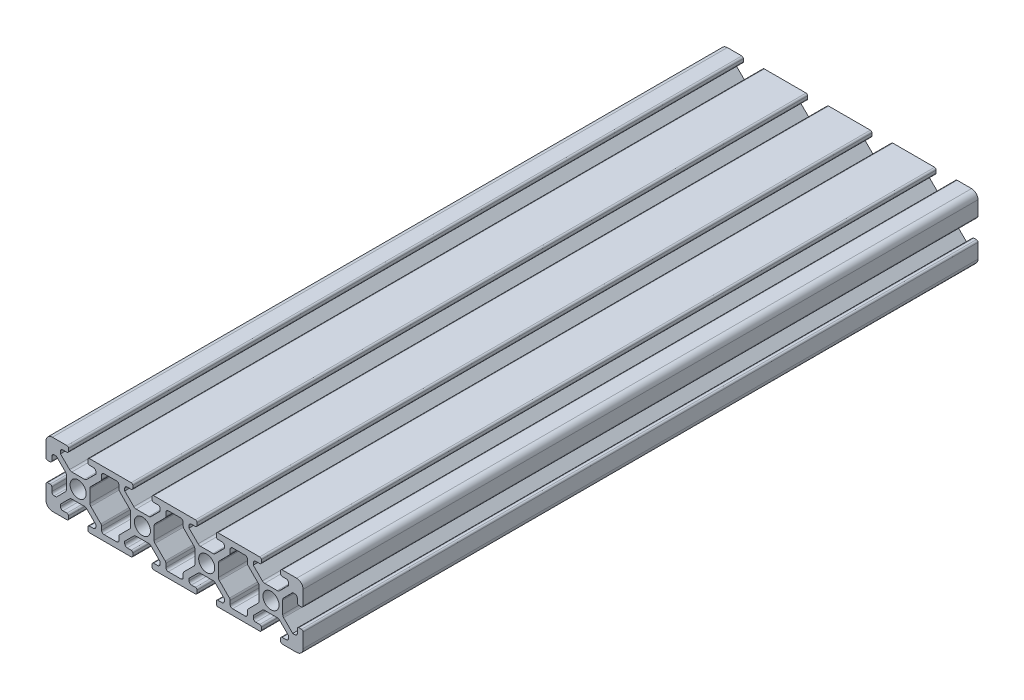
SolidWorks part; units mm, degrees
ref_plane "Front Plane" through (0, 0, 0) normal (0, 0, 1) x (1, 0, 0)
ref_plane "Top Plane" through (0, 0, 0) normal (0, 1, 0) x (1, 0, 0)
ref_plane "Right Plane" through (0, 0, 0) normal (1, 0, 0) x (0, 0, -1)
sketch "Sketch1" plane through (0, 0, 0) normal (0, 0, 1) x (1, 0, 0)
  line L0 (-38, -10) -> (-33.5, -10)
  line L1 (40, -8) -> (40, -3.5)
  line L2 (38, 10) -> (33.5, 10)
  line L3 (-40, 8) -> (-40, 3.5)
  line L4 (-7, 9.5) -> (-7, 8.7)
  line L5 (-13, 9.5) -> (-13, 8.7)
  line L6 (-33, 9.5) -> (-33, 8.7)
  line L7 (-27, 9.5) -> (-27, 8.7)
  line L8 (-33.5, 10) -> (-38, 10)
  line L9 (13, 9.5) -> (13, 8.7)
  line L10 (7, 9.5) -> (7, 8.7)
  line L11 (33, 9.5) -> (33, 8.7)
  line L12 (27, 9.5) -> (27, 8.7)
  line L13 (-7, -8.7) -> (-7, -9.5)
  line L14 (-13, -8.7) -> (-13, -9.5)
  line L15 (13, -8.7) -> (13, -9.5)
  line L16 (7, -8.7) -> (7, -9.5)
  line L17 (33, -8.7) -> (33, -9.5)
  line L18 (27, -8.7) -> (27, -9.5)
  line L19 (-27, -8.7) -> (-27, -9.5)
  line L20 (-33, -8.7) -> (-33, -9.5)
  line L21 (-26.5, 10) -> (-13.5, 10) construction
  line L22 (-13.5, 10) -> (-26.5, 10)
  line L23 (6.5, 10) -> (-6.5, 10)
  line L24 (26.5, 10) -> (13.5, 10)
  line L25 (33.5, -10) -> (38, -10)
  line L26 (13.5, -10) -> (26.5, -10)
  line L27 (-6.5, -10) -> (6.5, -10)
  line L28 (-26.5, -10) -> (-13.5, -10)
  line L29 (39.5, 3) -> (38.7, 3)
  line L30 (39.5, -3) -> (38.7, -3)
  line L31 (-39.5, 3) -> (-38.7, 3)
  line L32 (-39.5, -3) -> (-38.7, -3)
  line L33 (-40, -3.5) -> (-40, -8)
  line L34 (40, 3.5) -> (40, 8)
  line L35 (-38.2, 3.5) -> (-38.2, 4.75)
  line L36 (-34.75, 8.2) -> (-33.5, 8.2)
  line L37 (38.2, 4.75) -> (38.2, 3.5)
  line L38 (34.75, -8.2) -> (33.5, -8.2)
  line L39 (-38.2, -4.75) -> (-38.2, -3.5)
  line L40 (-26.5, 8.2) -> (-25.25, 8.2)
  line L41 (-33.5, -8.2) -> (-34.75, -8.2)
  line L42 (-6.5, 8.2) -> (-5.25, 8.2)
  line L43 (-13.5, -8.2) -> (-14.75, -8.2)
  line L44 (13.5, 8.2) -> (14.75, 8.2)
  line L45 (6.5, -8.2) -> (5.25, -8.2)
  line L46 (33.5, 8.2) -> (34.75, 8.2)
  line L47 (26.5, -8.2) -> (25.25, -8.2)
  line L48 (38.2, -3.5) -> (38.2, -4.75)
  line L49 (-27.3299, 3.9429) -> (-24.5, 6.7728)
  line L50 (-27.3299, -3.9429) -> (-24.5, -6.7728)
  line L51 (-7.3299, 3.9429) -> (-4.5, 6.7728)
  line L52 (-6.0571, 2.6701) -> (-2.9197, 5.8075)
  line L53 (-12.6701, 3.9429) -> (-15.5, 6.7728)
  line L54 (-17.0803, 5.8075) -> (-13.9429, 2.6701)
  line L55 (-12.6701, -3.9429) -> (-15.5, -6.7728)
  line L56 (-17.0803, -5.8075) -> (-13.9429, -2.6701)
  line L57 (7.3299, 3.9429) -> (4.5, 6.7728)
  line L58 (2.9197, 5.8075) -> (6.0571, 2.6701)
  line L59 (7.3299, -3.9429) -> (4.5, -6.7728)
  line L60 (2.9197, -5.8075) -> (6.0571, -2.6701)
  line L61 (27.3299, 3.9429) -> (24.5, 6.7728)
  line L62 (22.9197, 5.8075) -> (26.0571, 2.6701)
  line L63 (27.3299, -3.9429) -> (24.5, -6.7728)
  line L64 (22.9197, -5.8075) -> (26.0571, -2.6701)
  line L65 (-6.0571, -2.6701) -> (-2.9197, -5.8075)
  line L66 (-26.0571, 2.6701) -> (-22.9197, 5.8075)
  line L67 (-33.9429, -2.6701) -> (-36.7728, -5.5)
  line L68 (-32.6701, -3.9429) -> (-35.5, -6.7728)
  line L69 (-32.6701, 3.9429) -> (-35.5, 6.7728)
  line L70 (-7.3299, -3.9429) -> (-4.5, -6.7728)
  line L71 (-26.0571, -2.6701) -> (-22.9197, -5.8075)
  line L72 (12.6701, 3.9429) -> (15.5, 6.7728)
  line L73 (-33.9429, 2.6701) -> (-36.7728, 5.5)
  line L74 (13.9429, 2.6701) -> (17.0803, 5.8075)
  line L75 (13.9429, -2.6701) -> (17.0803, -5.8075)
  line L76 (12.6701, -3.9429) -> (15.5, -6.7728)
  line L77 (32.6701, 3.9429) -> (35.5, 6.7728)
  line L78 (33.9429, 2.6701) -> (36.7728, 5.5)
  line L79 (33.9429, -2.6701) -> (36.7728, -5.5)
  line L80 (32.6701, -3.9429) -> (35.5, -6.7728)
  line L81 (-11.963, 3.65) -> (-8.037, 3.65)
  line L82 (-21.95, 8.2) -> (-18.05, 8.2)
  line L83 (-25.25, -8.2) -> (-26.5, -8.2)
  line L84 (-24.5, 7.45) -> (-24.5, 6.7728)
  line L85 (-5.25, -8.2) -> (-6.5, -8.2)
  line L86 (-35.5, 7.45) -> (-35.5, 6.7728)
  line L87 (14.75, -8.2) -> (13.5, -8.2)
  line L88 (-15.5, 7.45) -> (-15.5, 6.7728)
  line L89 (-14.75, 8.2) -> (-13.5, 8.2)
  line L90 (5.25, 8.2) -> (6.5, 8.2)
  line L91 (-6.35, 1.963) -> (-6.35, -1.963)
  line L92 (-8.037, -3.65) -> (-11.963, -3.65)
  line L93 (-13.65, -1.963) -> (-13.65, 1.963)
  line L94 (25.25, 8.2) -> (26.5, 8.2)
  line L95 (4.5, 7.45) -> (4.5, 6.7728)
  line L96 (-4.5, 7.45) -> (-4.5, 6.7728)
  line L97 (-26.35, 1.963) -> (-26.35, -1.963)
  line L98 (-28.037, -3.65) -> (-31.963, -3.65)
  line L99 (-33.65, -1.963) -> (-33.65, 1.963)
  line L100 (-31.963, 3.65) -> (-28.037, 3.65)
  line L101 (8.037, 3.65) -> (11.963, 3.65)
  line L102 (13.65, 1.963) -> (13.65, -1.963)
  line L103 (11.963, -3.65) -> (8.037, -3.65)
  line L104 (6.35, -1.963) -> (6.35, 1.963)
  line L105 (28.037, 3.65) -> (31.963, 3.65)
  line L106 (33.65, 1.963) -> (33.65, -1.963)
  line L107 (31.963, -3.65) -> (28.037, -3.65)
  line L108 (26.35, -1.963) -> (26.35, 1.963)
  line L109 (24.5, 7.45) -> (24.5, 6.7728)
  line L110 (15.5, 7.45) -> (15.5, 6.7728)
  line L111 (-35.5, -7.45) -> (-35.5, -6.7728)
  line L112 (35.5, 7.45) -> (35.5, 6.7728)
  line L113 (-15.5, -7.45) -> (-15.5, -6.7728)
  line L114 (-24.5, -7.45) -> (-24.5, -6.7728)
  line L115 (4.5, -7.45) -> (4.5, -6.7728)
  line L116 (-4.5, -7.45) -> (-4.5, -6.7728)
  line L117 (24.5, -7.45) -> (24.5, -6.7728)
  line L118 (15.5, -7.45) -> (15.5, -6.7728)
  line L119 (-37.45, 5.5) -> (-36.7728, 5.5)
  line L120 (35.5, -7.45) -> (35.5, -6.7728)
  line L121 (-37.45, -5.5) -> (-36.7728, -5.5)
  line L122 (37.45, 5.5) -> (36.7728, 5.5)
  line L123 (-22.7, 7.45) -> (-22.7, 6.3379)
  line L124 (37.45, -5.5) -> (36.7728, -5.5)
  line L125 (-17.3, 7.45) -> (-17.3, 6.3379)
  line L126 (-1.95, 8.2) -> (1.95, 8.2)
  line L127 (-2.7, 7.45) -> (-2.7, 6.3379)
  line L128 (2.7, 7.45) -> (2.7, 6.3379)
  line L129 (18.05, 8.2) -> (21.95, 8.2)
  line L130 (17.3, 7.45) -> (17.3, 6.3379)
  line L131 (22.7, 7.45) -> (22.7, 6.3379)
  line L132 (-22.7, -6.3379) -> (-22.7, -7.45)
  line L133 (-21.95, -8.2) -> (-18.05, -8.2)
  line L134 (-17.3, -7.45) -> (-17.3, -6.3379)
  line L135 (-2.7, -6.3379) -> (-2.7, -7.45)
  line L136 (-1.95, -8.2) -> (1.95, -8.2)
  line L137 (2.7, -7.45) -> (2.7, -6.3379)
  line L138 (17.3, -6.3379) -> (17.3, -7.45)
  line L139 (18.05, -8.2) -> (21.95, -8.2)
  line L140 (22.7, -7.45) -> (22.7, -6.3379)
  circle A0 centre (-30, 0) radius 2.5
  circle A1 centre (-10, 0) radius 2.5
  circle A2 centre (10, 0) radius 2.5
  circle A3 centre (30, 0) radius 2.5
  arc A4 (38, -10) -> (40, -8) centre (38, -8) ccw
  arc A5 (40, 8) -> (38, 10) centre (38, 8) ccw
  arc A6 (-38, -10) -> (-40, -8) centre (-38, -8) cw
  arc A7 (-38, 10) -> (-40, 8) centre (-38, 8) ccw
  arc A8 (-27.3299, 3.9429) -> (-28.037, 3.65) centre (-28.037, 4.65) cw
  arc A9 (-32.6701, 3.9429) -> (-31.963, 3.65) centre (-31.963, 4.65) ccw
  arc A10 (-33.9429, 2.6701) -> (-33.65, 1.963) centre (-34.65, 1.963) cw
  arc A11 (-33.9429, -2.6701) -> (-33.65, -1.963) centre (-34.65, -1.963) ccw
  arc A12 (-32.6701, -3.9429) -> (-31.963, -3.65) centre (-31.963, -4.65) cw
  arc A13 (-27.3299, -3.9429) -> (-28.037, -3.65) centre (-28.037, -4.65) ccw
  arc A14 (-7.3299, -3.9429) -> (-8.037, -3.65) centre (-8.037, -4.65) ccw
  arc A15 (-12.6701, -3.9429) -> (-11.963, -3.65) centre (-11.963, -4.65) cw
  arc A16 (-12.6701, 3.9429) -> (-11.963, 3.65) centre (-11.963, 4.65) ccw
  arc A17 (-7.3299, 3.9429) -> (-8.037, 3.65) centre (-8.037, 4.65) cw
  arc A18 (7.3299, -3.9429) -> (8.037, -3.65) centre (8.037, -4.65) cw
  arc A19 (12.6701, -3.9429) -> (11.963, -3.65) centre (11.963, -4.65) ccw
  arc A20 (12.6701, 3.9429) -> (11.963, 3.65) centre (11.963, 4.65) cw
  arc A21 (7.3299, 3.9429) -> (8.037, 3.65) centre (8.037, 4.65) ccw
  arc A22 (32.6701, 3.9429) -> (31.963, 3.65) centre (31.963, 4.65) cw
  arc A23 (27.3299, 3.9429) -> (28.037, 3.65) centre (28.037, 4.65) ccw
  arc A24 (27.3299, -3.9429) -> (28.037, -3.65) centre (28.037, -4.65) cw
  arc A25 (32.6701, -3.9429) -> (31.963, -3.65) centre (31.963, -4.65) ccw
  arc A26 (33.9429, -2.6701) -> (33.65, -1.963) centre (34.65, -1.963) cw
  arc A27 (33.9429, 2.6701) -> (33.65, 1.963) centre (34.65, 1.963) ccw
  arc A28 (26.0571, -2.6701) -> (26.35, -1.963) centre (25.35, -1.963) ccw
  arc A29 (26.0571, 2.6701) -> (26.35, 1.963) centre (25.35, 1.963) cw
  arc A30 (13.9429, -2.6701) -> (13.65, -1.963) centre (14.65, -1.963) cw
  arc A31 (13.9429, 2.6701) -> (13.65, 1.963) centre (14.65, 1.963) ccw
  arc A32 (38.2, 4.75) -> (37.45, 5.5) centre (37.45, 4.75) ccw
  arc A33 (35.5, 7.45) -> (34.75, 8.2) centre (34.75, 7.45) ccw
  arc A34 (38.2, -4.75) -> (37.45, -5.5) centre (37.45, -4.75) cw
  arc A35 (35.5, -7.45) -> (34.75, -8.2) centre (34.75, -7.45) cw
  arc A36 (6.0571, -2.6701) -> (6.35, -1.963) centre (5.35, -1.963) ccw
  arc A37 (6.0571, 2.6701) -> (6.35, 1.963) centre (5.35, 1.963) cw
  arc A38 (-6.0571, -2.6701) -> (-6.35, -1.963) centre (-5.35, -1.963) cw
  arc A39 (-6.0571, 2.6701) -> (-6.35, 1.963) centre (-5.35, 1.963) ccw
  arc A40 (-26.0571, 2.6701) -> (-26.35, 1.963) centre (-25.35, 1.963) ccw
  arc A41 (-26.0571, -2.6701) -> (-26.35, -1.963) centre (-25.35, -1.963) cw
  arc A42 (-13.9429, -2.6701) -> (-13.65, -1.963) centre (-14.65, -1.963) ccw
  arc A43 (-13.9429, 2.6701) -> (-13.65, 1.963) centre (-14.65, 1.963) cw
  arc A44 (25.25, -8.2) -> (24.5, -7.45) centre (25.25, -7.45) cw
  arc A45 (21.95, -8.2) -> (22.7, -7.45) centre (21.95, -7.45) ccw
  arc A46 (17.3, -7.45) -> (18.05, -8.2) centre (18.05, -7.45) ccw
  arc A47 (14.75, -8.2) -> (15.5, -7.45) centre (14.75, -7.45) ccw
  arc A48 (5.25, -8.2) -> (4.5, -7.45) centre (5.25, -7.45) cw
  arc A49 (24.5, 7.45) -> (25.25, 8.2) centre (25.25, 7.45) cw
  arc A50 (21.95, 8.2) -> (22.7, 7.45) centre (21.95, 7.45) cw
  arc A51 (18.05, 8.2) -> (17.3, 7.45) centre (18.05, 7.45) ccw
  arc A52 (13, 8.7) -> (13.5, 8.2) centre (13.5, 8.7) ccw
  arc A53 (13, 9.5) -> (13.5, 10) centre (13.5, 9.5) cw
  arc A54 (27, 8.7) -> (26.5, 8.2) centre (26.5, 8.7) cw
  arc A55 (27, 9.5) -> (26.5, 10) centre (26.5, 9.5) ccw
  arc A56 (33, 8.7) -> (33.5, 8.2) centre (33.5, 8.7) ccw
  arc A57 (33, 9.5) -> (33.5, 10) centre (33.5, 9.5) cw
  arc A58 (38.7, 3) -> (38.2, 3.5) centre (38.7, 3.5) cw
  arc A59 (39.5, 3) -> (40, 3.5) centre (39.5, 3.5) ccw
  arc A60 (38.7, -3) -> (38.2, -3.5) centre (38.7, -3.5) ccw
  arc A61 (39.5, -3) -> (40, -3.5) centre (39.5, -3.5) cw
  arc A62 (33, -9.5) -> (33.5, -10) centre (33.5, -9.5) ccw
  arc A63 (33, -8.7) -> (33.5, -8.2) centre (33.5, -8.7) cw
  arc A64 (27, -9.5) -> (26.5, -10) centre (26.5, -9.5) cw
  arc A65 (27, -8.7) -> (26.5, -8.2) centre (26.5, -8.7) ccw
  arc A66 (13, -9.5) -> (13.5, -10) centre (13.5, -9.5) ccw
  arc A67 (13, -8.7) -> (13.5, -8.2) centre (13.5, -8.7) cw
  arc A68 (7, -9.5) -> (6.5, -10) centre (6.5, -9.5) cw
  arc A69 (7, -8.7) -> (6.5, -8.2) centre (6.5, -8.7) ccw
  arc A70 (-7, -9.5) -> (-6.5, -10) centre (-6.5, -9.5) ccw
  arc A71 (-7, -8.7) -> (-6.5, -8.2) centre (-6.5, -8.7) cw
  arc A72 (-13, -9.5) -> (-13.5, -10) centre (-13.5, -9.5) cw
  arc A73 (-13, -8.7) -> (-13.5, -8.2) centre (-13.5, -8.7) ccw
  arc A74 (7, 8.7) -> (6.5, 8.2) centre (6.5, 8.7) cw
  arc A75 (7, 9.5) -> (6.5, 10) centre (6.5, 9.5) ccw
  arc A76 (-7, 8.7) -> (-6.5, 8.2) centre (-6.5, 8.7) ccw
  arc A77 (-7, 9.5) -> (-6.5, 10) centre (-6.5, 9.5) cw
  arc A78 (-13, 8.7) -> (-13.5, 8.2) centre (-13.5, 8.7) cw
  arc A79 (-13, 9.5) -> (-13.5, 10) centre (-13.5, 9.5) ccw
  arc A80 (-27, 8.7) -> (-26.5, 8.2) centre (-26.5, 8.7) ccw
  arc A81 (-26.5, 10) -> (-27, 9.5) centre (-26.5, 9.5) ccw
  arc A82 (-27, -9.5) -> (-26.5, -10) centre (-26.5, -9.5) ccw
  arc A83 (-27, -8.7) -> (-26.5, -8.2) centre (-26.5, -8.7) cw
  arc A84 (-33, -9.5) -> (-33.5, -10) centre (-33.5, -9.5) cw
  arc A85 (-33, -8.7) -> (-33.5, -8.2) centre (-33.5, -8.7) ccw
  arc A86 (-40, -3.5) -> (-39.5, -3) centre (-39.5, -3.5) cw
  arc A87 (-38.7, -3) -> (-38.2, -3.5) centre (-38.7, -3.5) cw
  arc A88 (-40, 3.5) -> (-39.5, 3) centre (-39.5, 3.5) ccw
  arc A89 (-38.7, 3) -> (-38.2, 3.5) centre (-38.7, 3.5) ccw
  arc A90 (-33.5, 10) -> (-33, 9.5) centre (-33.5, 9.5) cw
  arc A91 (-33, 8.7) -> (-33.5, 8.2) centre (-33.5, 8.7) cw
  arc A92 (15.5, 7.45) -> (14.75, 8.2) centre (14.75, 7.45) ccw
  arc A93 (4.5, 7.45) -> (5.25, 8.2) centre (5.25, 7.45) cw
  arc A94 (-2.7, -7.45) -> (-1.95, -8.2) centre (-1.95, -7.45) ccw
  arc A95 (-1.95, 8.2) -> (-2.7, 7.45) centre (-1.95, 7.45) ccw
  arc A96 (1.95, 8.2) -> (2.7, 7.45) centre (1.95, 7.45) cw
  arc A97 (1.95, -8.2) -> (2.7, -7.45) centre (1.95, -7.45) ccw
  arc A98 (-5.25, -8.2) -> (-4.5, -7.45) centre (-5.25, -7.45) ccw
  arc A99 (-14.75, -8.2) -> (-15.5, -7.45) centre (-14.75, -7.45) cw
  arc A100 (-25.25, -8.2) -> (-24.5, -7.45) centre (-25.25, -7.45) ccw
  arc A101 (-34.75, -8.2) -> (-35.5, -7.45) centre (-34.75, -7.45) cw
  arc A102 (-37.45, -5.5) -> (-38.2, -4.75) centre (-37.45, -4.75) cw
  arc A103 (-38.2, 4.75) -> (-37.45, 5.5) centre (-37.45, 4.75) cw
  arc A104 (-15.5, 7.45) -> (-14.75, 8.2) centre (-14.75, 7.45) cw
  arc A105 (-5.25, 8.2) -> (-4.5, 7.45) centre (-5.25, 7.45) cw
  arc A106 (-18.05, 8.2) -> (-17.3, 7.45) centre (-18.05, 7.45) cw
  arc A107 (-21.95, 8.2) -> (-22.7, 7.45) centre (-21.95, 7.45) ccw
  arc A108 (-24.5, 7.45) -> (-25.25, 8.2) centre (-25.25, 7.45) ccw
  arc A109 (-34.75, 8.2) -> (-35.5, 7.45) centre (-34.75, 7.45) ccw
  arc A110 (22.7, -6.3379) -> (22.9197, -5.8075) centre (23.45, -6.3379) cw
  arc A111 (17.3, -6.3379) -> (17.0803, -5.8075) centre (16.55, -6.3379) ccw
  arc A112 (22.7, 6.3379) -> (22.9197, 5.8075) centre (23.45, 6.3379) ccw
  arc A113 (17.3, 6.3379) -> (17.0803, 5.8075) centre (16.55, 6.3379) cw
  arc A114 (2.7, -6.3379) -> (2.9197, -5.8075) centre (3.45, -6.3379) cw
  arc A115 (-2.7, -6.3379) -> (-2.9197, -5.8075) centre (-3.45, -6.3379) ccw
  arc A116 (2.7, 6.3379) -> (2.9197, 5.8075) centre (3.45, 6.3379) ccw
  arc A117 (-2.7, 6.3379) -> (-2.9197, 5.8075) centre (-3.45, 6.3379) cw
  arc A118 (-17.3, 6.3379) -> (-17.0803, 5.8075) centre (-16.55, 6.3379) ccw
  arc A119 (-22.7, 6.3379) -> (-22.9197, 5.8075) centre (-23.45, 6.3379) cw
  arc A120 (-22.7, -6.3379) -> (-22.9197, -5.8075) centre (-23.45, -6.3379) ccw
  arc A121 (-17.3, -6.3379) -> (-17.0803, -5.8075) centre (-16.55, -6.3379) cw
  arc A122 (-18.05, -8.2) -> (-17.3, -7.45) centre (-18.05, -7.45) ccw
  arc A123 (-22.7, -7.45) -> (-21.95, -8.2) centre (-21.95, -7.45) ccw
extrude "Boss-Extrude1" add sketch "Sketch1" along normal blind 210
